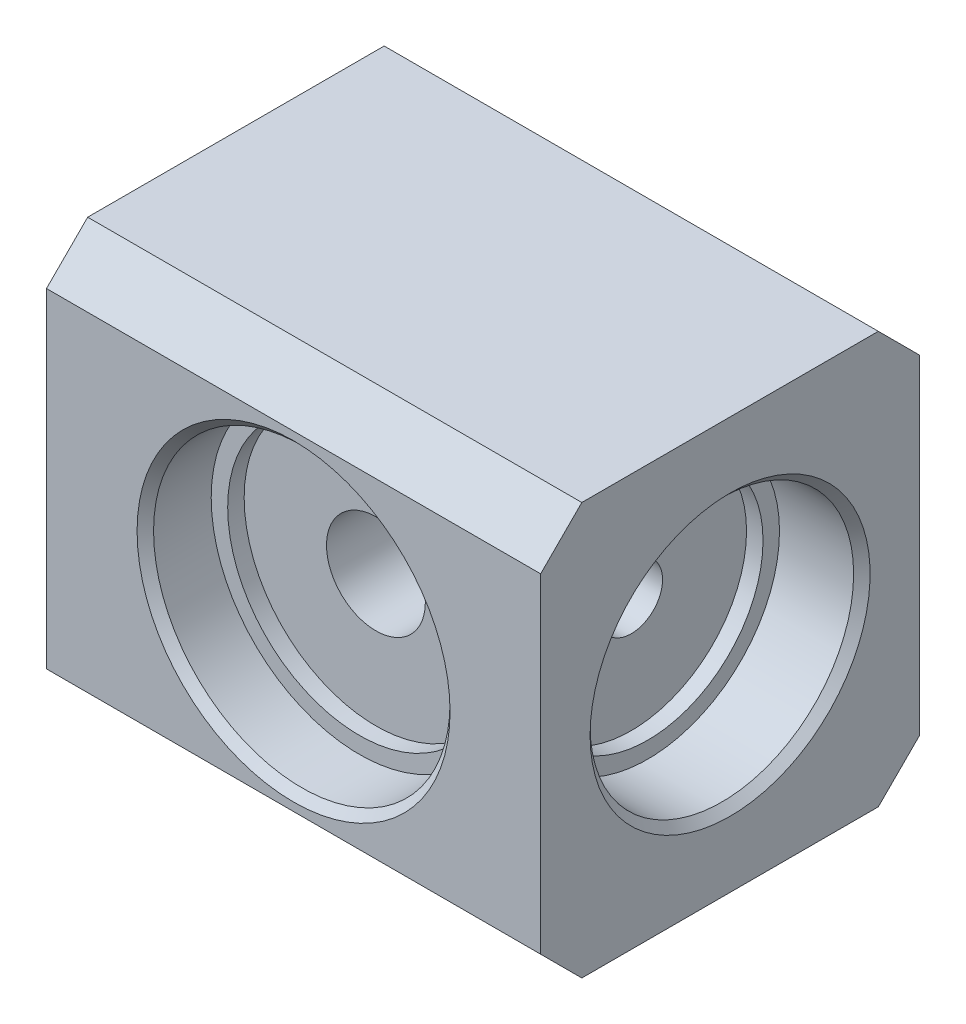
SolidWorks part; units mm, degrees
material "PLA"
ref_plane "Front Plane" through (0, 0, 0) normal (0, 0, 1) x (1, 0, 0)
ref_plane "Top Plane" through (0, 0, 0) normal (0, 1, 0) x (1, 0, 0)
ref_plane "Right Plane" through (0, 0, 0) normal (1, 0, 0) x (0, 0, -1)
sketch "Sketch1" plane through (0, 0, 0) normal (0, 1, 0) x (1, 0, 0)
  line L0 (0, 0) -> (30, 0) construction
  line L2 (0, 12.5) -> (30, 12.5)
  line L3 (0, 12.5) -> (0, -10.5)
  line L4 (0, -10.5) -> (30, -10.5)
  line L5 (30, 12.5) -> (30, -10.5)
  dimension "D1" = 30
  dimension "D2" = 12.5
  dimension "D3" = 23
extrude "Boss-Extrude1" add sketch "Sketch1" along normal blind 25
sketch "Sketch2" plane through (30, 0, 0) normal (1, 0, 0) x (0, 0, -1)
  line L0 (-10.5, 25) -> (12.5, 0) construction
  circle A0 centre (1, 12.5) radius 8
  dimension "D1" = 16
extrude "Cut-Extrude1" cut sketch "Sketch2" against normal blind 5
sketch "Sketch3" plane through (25, 0, 0) normal (1, 0, 0) x (0, 0, -1)
  circle A0 centre (1, 12.5) radius 7
  dimension "D1" = 14
extrude "Cut-Extrude2" cut sketch "Sketch3" against normal blind 1
sketch "Sketch4" plane through (24, 0, 0) normal (1, 0, 0) x (0, 0, -1)
  circle A0 centre (1, 12.5) radius 1.9
  dimension "D1" = 3.8
extrude "Cut-Extrude3" cut sketch "Sketch4" against normal blind 4
sketch "Sketch5" plane through (0, 25, 0) normal (0, 1, 0) x (1, 0, 0)
  line L0 (0, 0) -> (15, 0) construction
  dimension "D1" = 15
ref_plane "Plane1" through (15, 25, 0) normal (1, 0, 0) x (0, 0, -1)
mirror "Mirror1" about plane through (15, 25, 0) normal (1, 0, 0) of "Cut-Extrude3", "Cut-Extrude2", "Cut-Extrude1"
sketch "Sketch6" plane through (0, 0, 10.5) normal (0, 0, 1) x (1, 0, 0)
  line L0 (0, 25) -> (30, 0) construction
  circle A0 centre (15, 12.5) radius 9
  dimension "D1" = 18
extrude "Cut-Extrude4" cut sketch "Sketch6" against normal blind 4
sketch "Sketch7" plane through (0, 0, 6.5) normal (0, 0, 1) x (1, 0, 0)
  circle A0 centre (15, 12.5) radius 3
  dimension "D1" = 6
sketch "Sketch10" plane through (0, 0, 0) normal (0, -1, 0) x (1, 0, 0)
  line L0 (15, -12.5) -> (15, -1) construction
  line L1 (30, -12.5) -> (0, -12.5) construction
  dimension "D1" = 11.5
ref_plane "Plane2" through (15, 0, -1) normal (0, 0, 1) x (1, 0, 0)
extrude "Cut-Extrude8" cut sketch "Sketch7" against normal up to surface (19 mm away) up to face at (15, 12.5, -12.5)
sketch "Sketch12" plane through (0, 0, 6.5) normal (0, 0, 1) x (1, 0, 0)
  circle A0 centre (15, 12.5) radius 8
  dimension "D1" = 16
extrude "Cut-Extrude9" cut sketch "Sketch12" against normal blind 1
mirror "Mirror4" about plane through (15, 0, -1) normal (0, 0, 1) of "Cut-Extrude4", "Cut-Extrude9"
chamfer "Chamfer1" distance 2.5 angle 45 4 edges at (15, 0, -12.5) (15, 0, 10.5) (15, 25, 10.5) (15, 25, -12.5)
chamfer "Chamfer2" distance 0.5 angle 45 4 edges at (0, 12.5, -9) (30, 12.5, -9) (24, 12.5, -12.5) (24, 12.5, 10.5)
